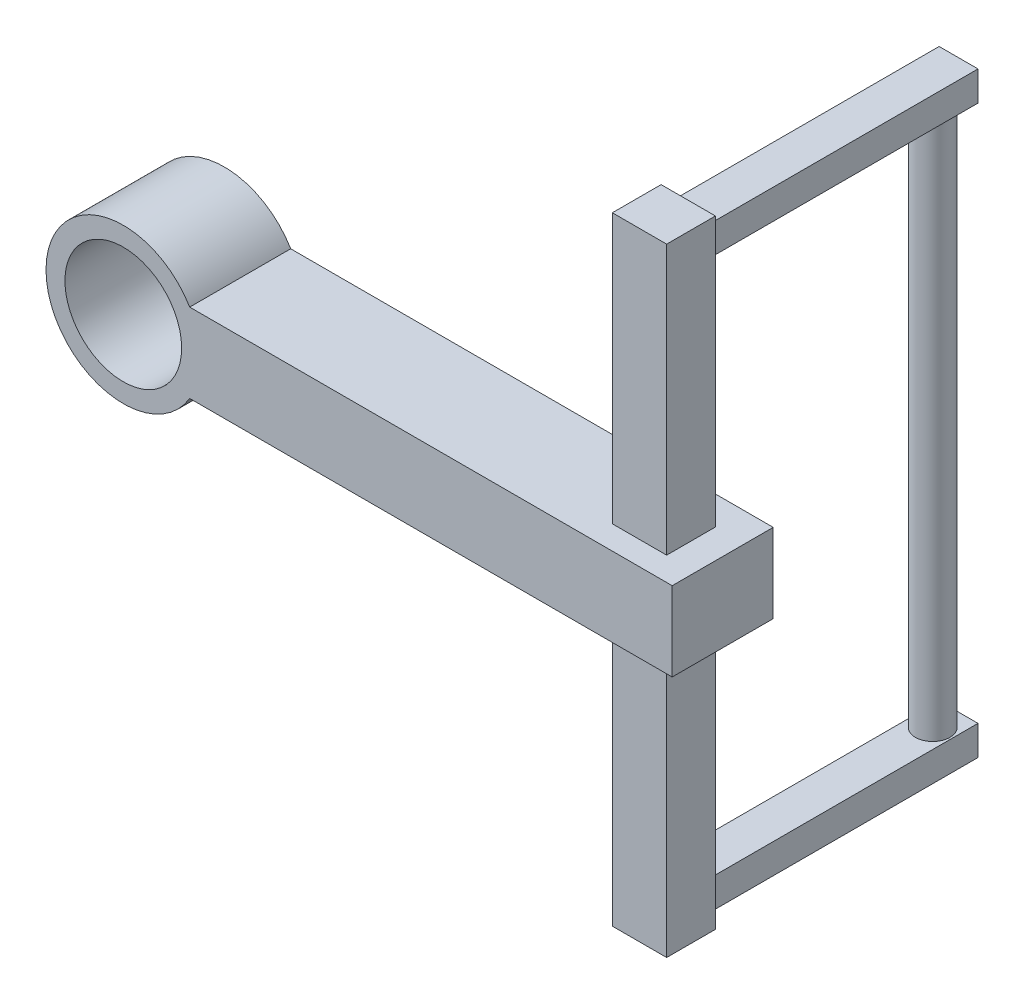
SolidWorks part; units mm, degrees
ref_plane "Front Plane" through (0, 0, 0) normal (0, 0, 1) x (1, 0, 0)
ref_plane "Top Plane" through (0, 0, 0) normal (0, 1, 0) x (1, 0, 0)
ref_plane "Right Plane" through (0, 0, 0) normal (1, 0, 0) x (0, 0, -1)
sketch "Sketch1" plane through (0, 0, 0) normal (0, 0, 1) x (1, 0, 0)
  line L1 (19.7215, 11.7455) -> (163.0159, 11.7455)
  line L3 (19.7215, -11.7455) -> (163.0159, -11.7455)
  line L4 (163.0159, 11.7455) -> (163.0159, -11.7455)
  circle A0 centre (0, 0) radius 17.3264
  arc A1 (19.7215, 11.7455) -> (19.7215, -11.7455) centre (0, 0) ccw
  point P8 (0, 0)
extrude "Boss-Extrude1" add sketch "Sketch1" along normal blind 30
sketch "Sketch3" plane through (0, 11.7455, 0) normal (0, 1, 0) x (1, 0, 0)
  line L1 (138.2165, -8.493) -> (154.3465, -8.493)
  line L2 (138.2165, -8.493) -> (138.2165, -22.9733)
  line L3 (138.2165, -22.9733) -> (154.3465, -22.9733)
  line L4 (154.3465, -8.493) -> (154.3465, -22.9733)
extrude "Boss-Extrude2" add sketch "Sketch3" along normal blind 80
sketch "Sketch4" plane through (0, 0, 8.493) normal (0, 0, -1) x (-1, 0, 0)
  line L1 (-152.3302, 88.5593) -> (-140.7827, 88.5593)
  line L2 (-152.3302, 88.5593) -> (-152.3302, 79.7611)
  line L3 (-152.3302, 79.7611) -> (-140.7827, 79.7611)
  line L4 (-140.7827, 88.5593) -> (-140.7827, 79.7611)
extrude "Boss-Extrude3" add sketch "Sketch4" along normal blind 80
mirror "Mirror1" about plane through (0, 0, 0) normal (0, 1, 0) of "Boss-Extrude3", "Boss-Extrude2"
sketch "Sketch5" plane through (0, -79.7611, 0) normal (0, 1, 0) x (1, 0, 0)
  circle A0 centre (146.6481, 63.7361) radius 5.1355
extrude "Boss-Extrude4" add sketch "Sketch5" along normal blind 162
